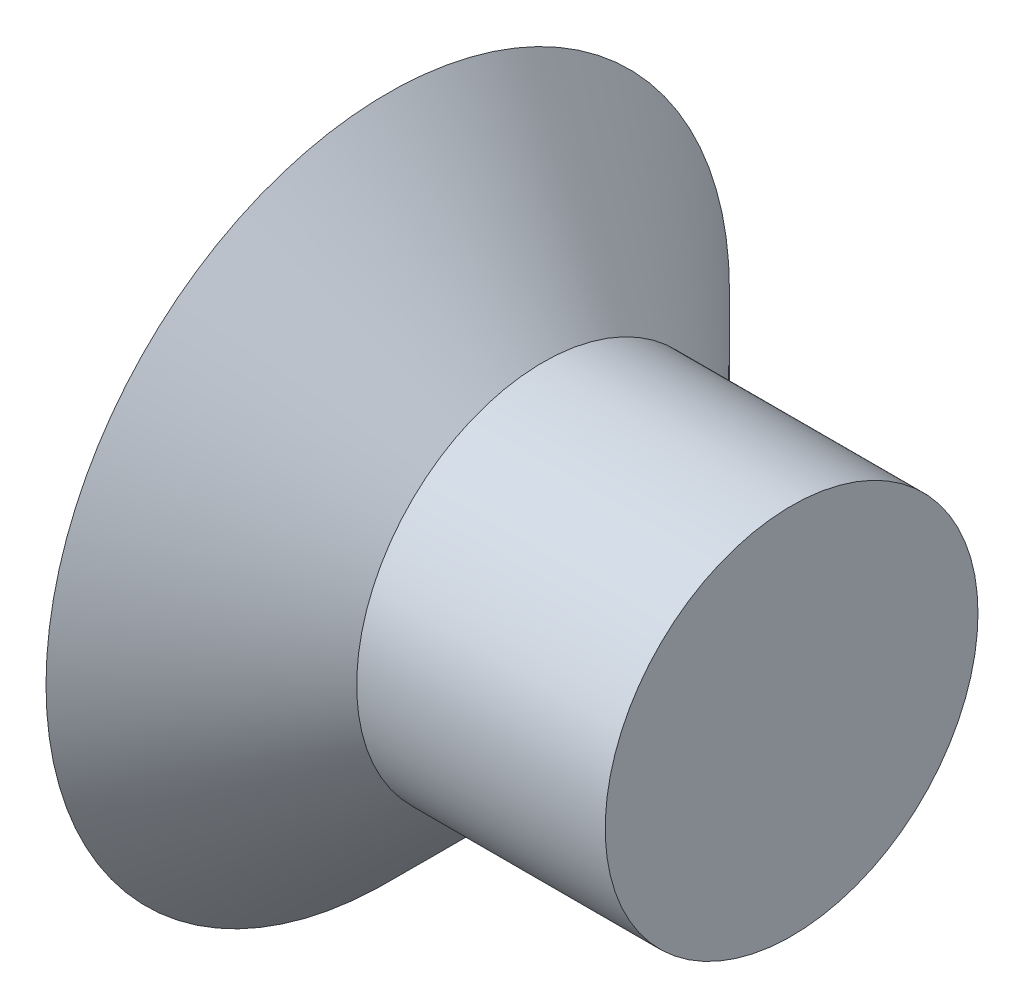
SolidWorks part; units mm, degrees
ref_plane "Front Plane" through (0, 0, 0) normal (0, 0, 1) x (1, 0, 0)
ref_plane "Top Plane" through (0, 0, 0) normal (0, 1, 0) x (1, 0, 0)
ref_plane "Right Plane" through (0, 0, 0) normal (1, 0, 0) x (0, 0, -1)
sketch "Sketch2" plane through (0, 0, 0) normal (0, 0, 1) x (1, 0, 0)
  line L0 (0, 0) -> (0, 11)
  line L1 (0, 11) -> (5, 6)
  line L2 (5, 6) -> (13, 6)
  line L3 (13, 6) -> (13, 0)
  line L4 (13, 0) -> (0, 0)
  point P6 (6.8648, 5.1352)
  dimension "D1" = 45
  dimension "D2" = 11
  dimension "D3" = 6
  dimension "D4" = 8
revolve "Revolve1" add sketch "Sketch2" angle 360 about L4
